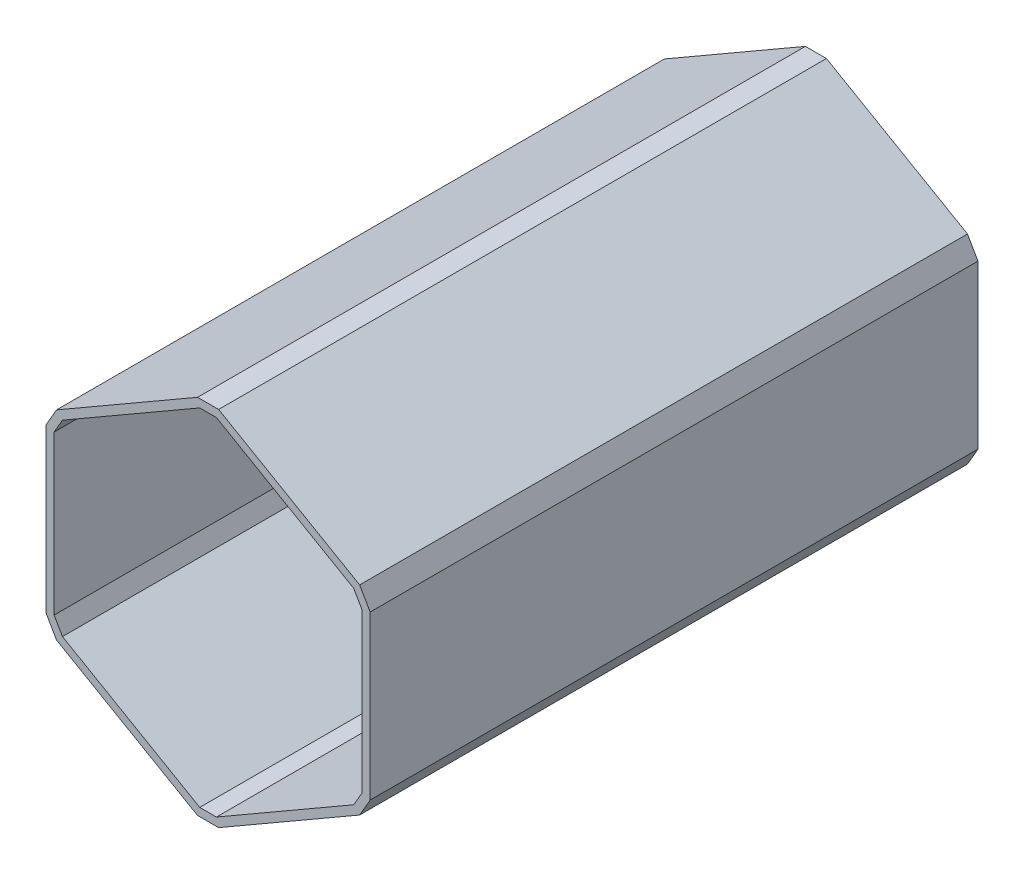
SolidWorks part; units mm, degrees
material "ABS"
ref_plane "Спереди" through (0, 0, 0) normal (0, 0, 1) x (1, 0, 0)
ref_plane "Сверху" through (0, 0, 0) normal (0, 1, 0) x (1, 0, 0)
ref_plane "Справа" through (0, 0, 0) normal (1, 0, 0) x (0, 0, -1)
sketch "Эскиз1" plane through (0, 0, 0) normal (0, 0, 1) x (1, 0, 0)
  line L0 (2.5981, 44.688) -> (-2.5981, 44.688)
  line L1 (40, -20.094) -> (40, 20.094)
  line L2 (37.4019, 24.594) -> (2.5981, 44.688)
  line L3 (-2.5981, 44.688) -> (-37.4019, 24.594)
  line L4 (-40, 20.094) -> (-40, -20.094)
  line L5 (-37.4019, -24.594) -> (-2.5981, -44.688)
  line L6 (2.5981, -44.688) -> (37.4019, -24.594)
  line L7 (-37.4019, 24.594) -> (-40, 20.094)
  line L8 (-40, -20.094) -> (-37.4019, -24.594)
  line L9 (37.4019, -24.594) -> (40, -20.094)
  line L10 (40, 20.094) -> (37.4019, 24.594)
  line L11 (-2.5981, -44.688) -> (2.5981, -44.688)
  line L12 (-2.0622, 42.688) -> (-35.9378, 23.1299)
  line L13 (-35.9378, 23.1299) -> (-38, 19.5581)
  line L14 (-38, 19.5581) -> (-38, -19.5581)
  line L15 (-38, -19.5581) -> (-35.9378, -23.1299)
  line L16 (-35.9378, -23.1299) -> (-2.0622, -42.688)
  line L17 (-2.0622, -42.688) -> (2.0622, -42.688)
  line L18 (2.0622, -42.688) -> (35.9378, -23.1299)
  line L19 (35.9378, -23.1299) -> (38, -19.5581)
  line L20 (38, -19.5581) -> (38, 19.5581)
  line L21 (38, 19.5581) -> (35.9378, 23.1299)
  line L22 (35.9378, 23.1299) -> (2.0622, 42.688)
  line L23 (2.0622, 42.688) -> (-2.0622, 42.688)
  circle A0 centre (0, 0) radius 40 construction
  point P2 (40, -23.094)
  point P3 (40, 23.094)
  point P4 (0, 46.188)
  point P5 (-40, 23.094)
  point P6 (-40, -23.094)
  point P7 (0, -46.188)
  dimension "D1" = 80
  dimension "D2" = 2
extrude "Бобышка-Вытянуть1" add sketch "Эскиз1" along normal blind 150
